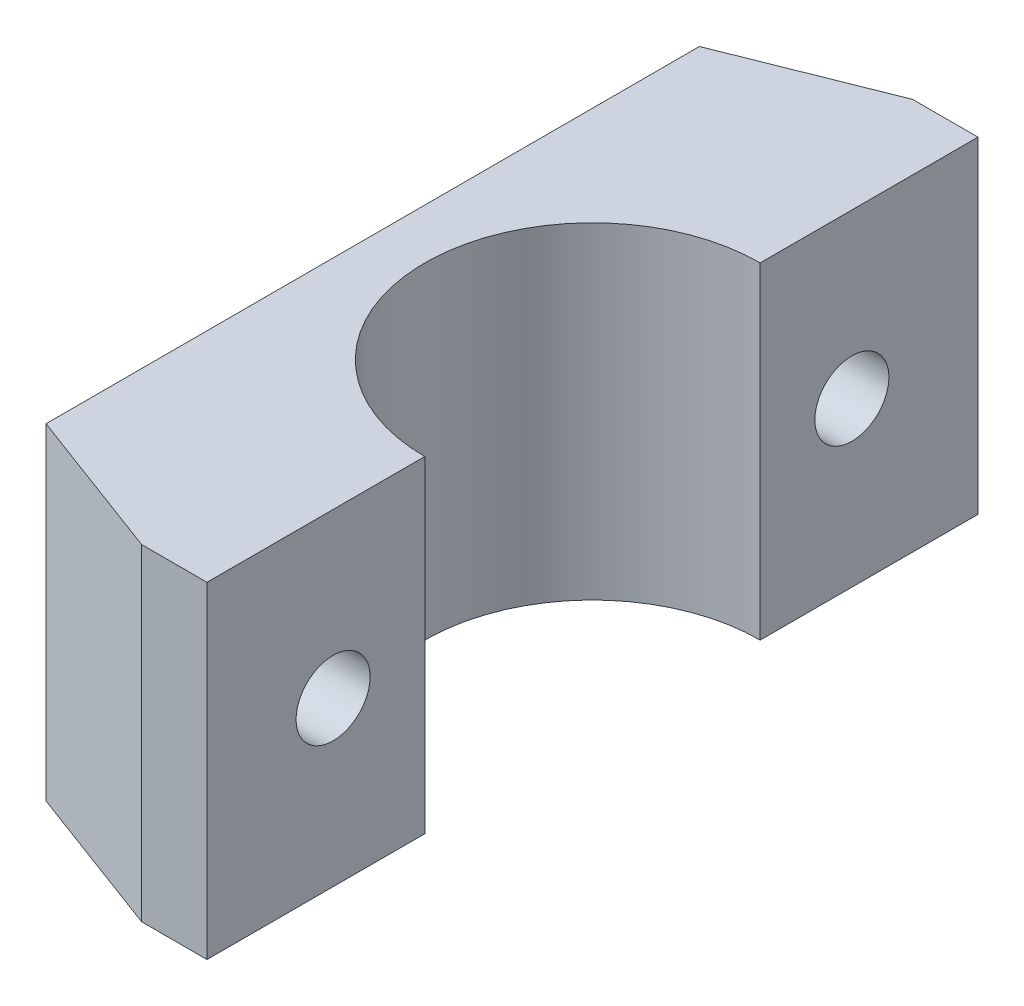
SolidWorks part; units mm, degrees
material "ABS"
ref_plane "Front Plane" through (0, 0, 0) normal (0, 0, 1) x (1, 0, 0)
ref_plane "Top Plane" through (0, 0, 0) normal (0, 1, 0) x (1, 0, 0)
ref_plane "Right Plane" through (0, 0, 0) normal (1, 0, 0) x (0, 0, -1)
sketch "Sketch1" plane through (0, 0, 0) normal (0, 1, 0) x (1, 0, 0)
  line L0 (0, 7.7) -> (0, 17.7)
  line L1 (0, 17.7) -> (-3, 17.7)
  line L2 (-3, 17.7) -> (-10, 14.9092)
  line L3 (-10, 14.9092) -> (-10, -15.0908)
  line L4 (-10, -15.0908) -> (-3, -17.7)
  line L5 (-3, -17.7) -> (0, -17.7)
  line L6 (0, -17.7) -> (0, -7.7)
  arc A0 (0, 7.7) -> (0, -7.7) centre (0, 0) ccw
  point P1 (-3, 20.3589)
  point P10 (-8.6118, 16.5129)
  point P12 (-5.769, 19.1047)
  dimension "D1" = 15.4
  dimension "D2" = 10
  dimension "D3" = 30
  dimension "D4" = 3
  dimension "D5" = 10
extrude "Boss-Extrude1" add sketch "Sketch1" along normal blind 15
sketch "Sketch2" plane through (-10, 0, 0) normal (-1, 0, 0) x (0, 0, 1)
  line L0 (17.7, 7.5) -> (-17.7, 7.5) construction
  line L1 (17.7, 15) -> (17.7, 0) construction
  line L2 (-17.7, 15) -> (-17.7, 0) construction
  line L3 (-14.9092, 15) -> (-14.9092, 0) construction
  line L4 (0, -992.5) -> (0, 49007.5) construction
  circle A0 centre (-11.9092, 7.5) radius 1.7
  circle A1 centre (11.9092, 7.5) radius 1.7
  point P14 (0, 7.5)
  dimension "D1" = 3.4
  dimension "D2" = 3
extrude "Cut-Extrude1" cut sketch "Sketch2" against normal blind 15
